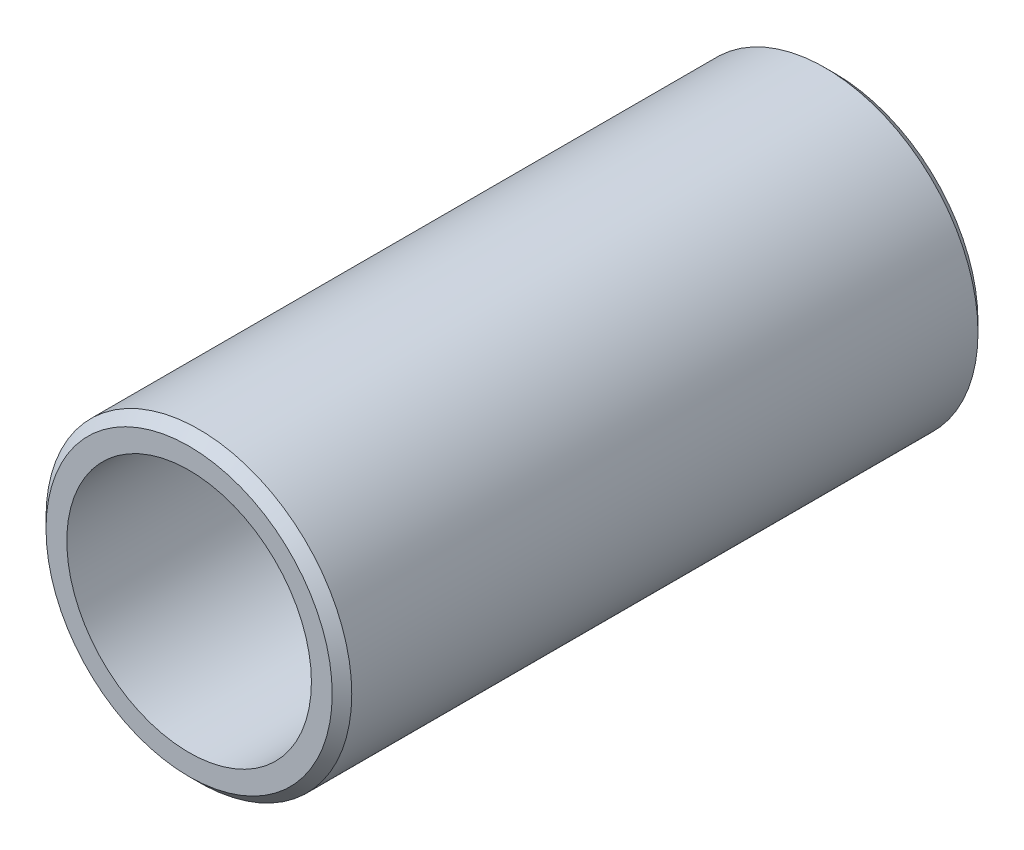
SolidWorks part; units mm, degrees
material "6061-T6 (SS)"
ref_plane "Front Plane" through (0, 0, 0) normal (0, 0, 1) x (1, 0, 0)
ref_plane "Top Plane" through (0, 0, 0) normal (0, 1, 0) x (1, 0, 0)
ref_plane "Right Plane" through (0, 0, 0) normal (1, 0, 0) x (0, 0, -1)
sketch "Sketch1" plane through (0, 0, 0) normal (0, 0, 1) x (1, 0, 0)
  circle A0 centre (0, 0) radius 6.35
  circle A1 centre (0, 0) radius 7.9375
  dimension "D1" = 12.7
  dimension "D2" = 15.875
extrude "Boss-Extrude1" add sketch "Sketch1" along normal blind 33.528
chamfer "Chamfer1" distance 0.508 angle 45 2 edges at (7.9375, 0, 0) (7.9375, 0, 33.528)
